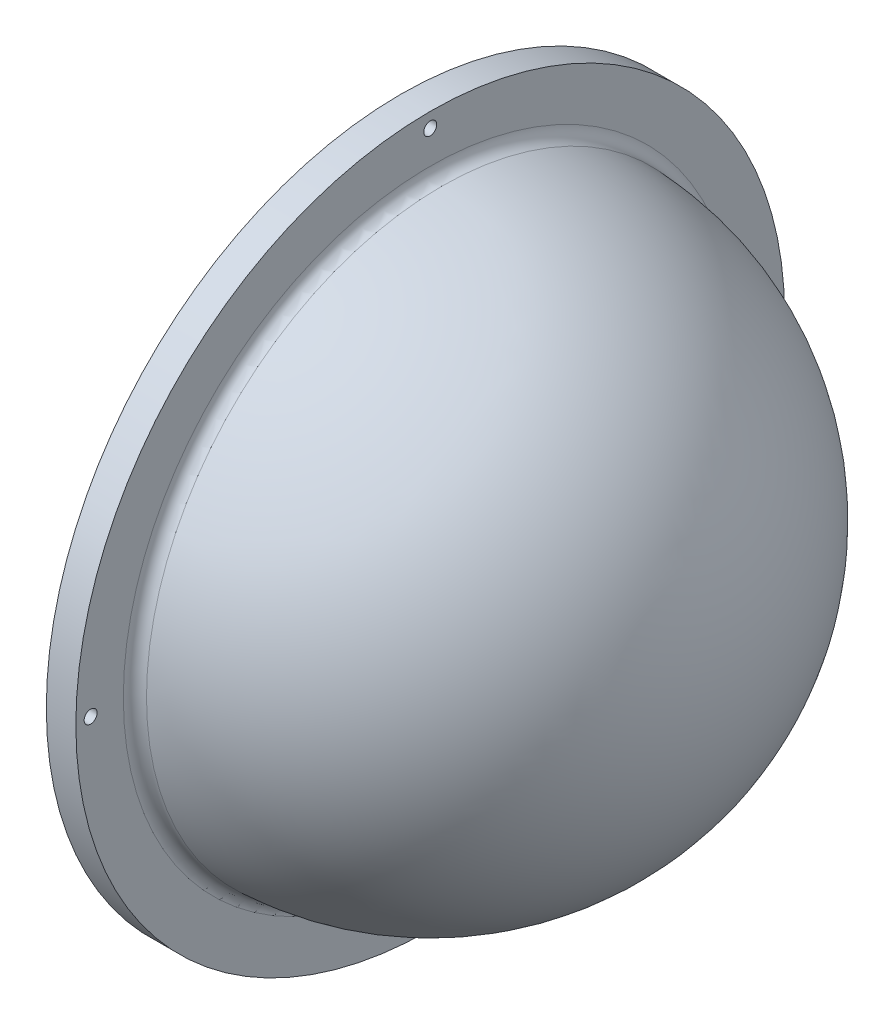
SolidWorks part; units mm, degrees
material "Acrylic (Medium-high impact)"
ref_plane "Front Plane" through (0, 0, 0) normal (0, 0, 1) x (1, 0, 0)
ref_plane "Top Plane" through (0, 0, 0) normal (0, 1, 0) x (1, 0, 0)
ref_plane "Right Plane" through (0, 0, 0) normal (1, 0, 0) x (0, 0, -1)
sketch "Sketch1" plane through (0, 0, 0) normal (0, 0, 1) x (1, 0, 0)
  line L0 (0, 80.1738) -> (0, -81.9526) construction
  line L1 (-122.4842, 0) -> (0, 0) construction
  line L2 (0, 76.2) -> (6.35, 76.2)
  line L3 (6.35, 76.2) -> (6.35, 63.5)
  line L4 (0, 76.2) -> (0, 57.15)
  line L5 (0, 0) -> (129.0913, 0) construction
  line L6 (6.35, 86.1997) -> (6.35, -57.7723) construction
  line L7 (0, 57.15) -> (6.35, 57.15)
  line L8 (69.85, 0) -> (63.5, 0)
  arc A0 (69.85, 0) -> (6.35, 63.5) centre (6.35, 0) ccw
  arc A2 (63.5, 0) -> (6.35, 57.15) centre (6.35, 0) ccw
  point P5 (0, 76.2)
revolve "Revolve1" add sketch "Sketch1" angle 360 about L5
fillet "Fillet1" radius 2.54 1 edges at (6.35, 0, 63.5)
sketch "Sketch2" plane through (6.35, 0, 0) normal (1, 0, 0) x (0, 0, -1)
  line L0 (0, 81.0184) -> (0, -81.6163) construction
  line L1 (-121.1788, 0) -> (116.9933, 0) construction
  circle A0 centre (0, 73.025) radius 1.3952
  circle A1 centre (73.025, 0) radius 1.3952
  circle A2 centre (0, -73.025) radius 1.3952
  circle A3 centre (-73.025, 0) radius 1.3952
  point P16 (0, 0)
  dimension "D1" = 4
extrude "Cut-Extrude1" cut sketch "Sketch2" against normal through all
